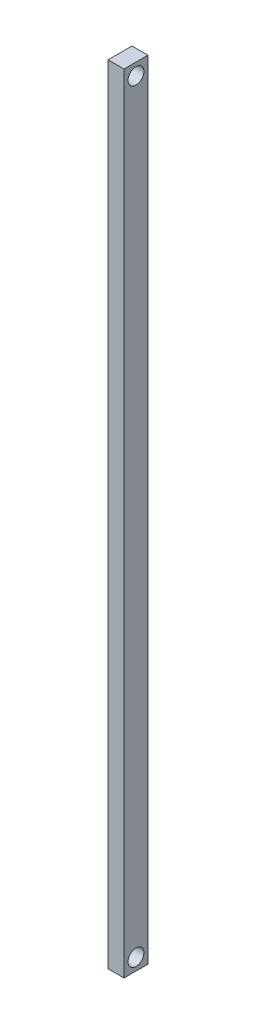
SolidWorks part; units mm, degrees
material "Plain Carbon Steel"
ref_plane "Front Plane" through (0, 0, 0) normal (1, 0, 0) x (0, 1, 0)
ref_plane "Top Plane" through (0, 0, 0) normal (0, 0, 1) x (0, 1, 0)
ref_plane "Right Plane" through (0, 0, 0) normal (0, 1, 0) x (-1, 0, 0)
sketch "Sketch1" plane through (0, 0, 0) normal (1, 0, 0) x (0, 1, 0)
  line L0 (0, 0) -> (494, 0)
  line L1 (494, 0) -> (494, 15)
  line L2 (494, 15) -> (0, 15)
  line L3 (0, 15) -> (0, 0)
  dimension "D1" = 15
  dimension "D2" = 494
extrude "Boss-Extrude1" add sketch "Sketch1" along normal blind 10
sketch "Sketch3" plane through (0, 0, 0) normal (1, 0, 0) x (0, 1, 0)
  line L0 (494, 15) -> (0, 15) construction
  line L1 (0, 15) -> (0, 0) construction
  circle A0 centre (7.5, 7.5) radius 5
  dimension "D1" = 10
  dimension "D2" = 7.5
  dimension "D3" = 7.5
extrude "Cut-Extrude1" cut sketch "Sketch3" along normal blind 10
sketch "Sketch4" plane through (10, 0, 0) normal (1, 0, 0) x (0, 1, 0)
  line L0 (494, 15) -> (0, 15) construction
  line L1 (494, 0) -> (494, 15) construction
  circle A0 centre (486.5, 7.5) radius 5
  dimension "D1" = 10
  dimension "D2" = 7.5
  dimension "D3" = 7.5
extrude "Cut-Extrude2" cut sketch "Sketch4" against normal blind 10
